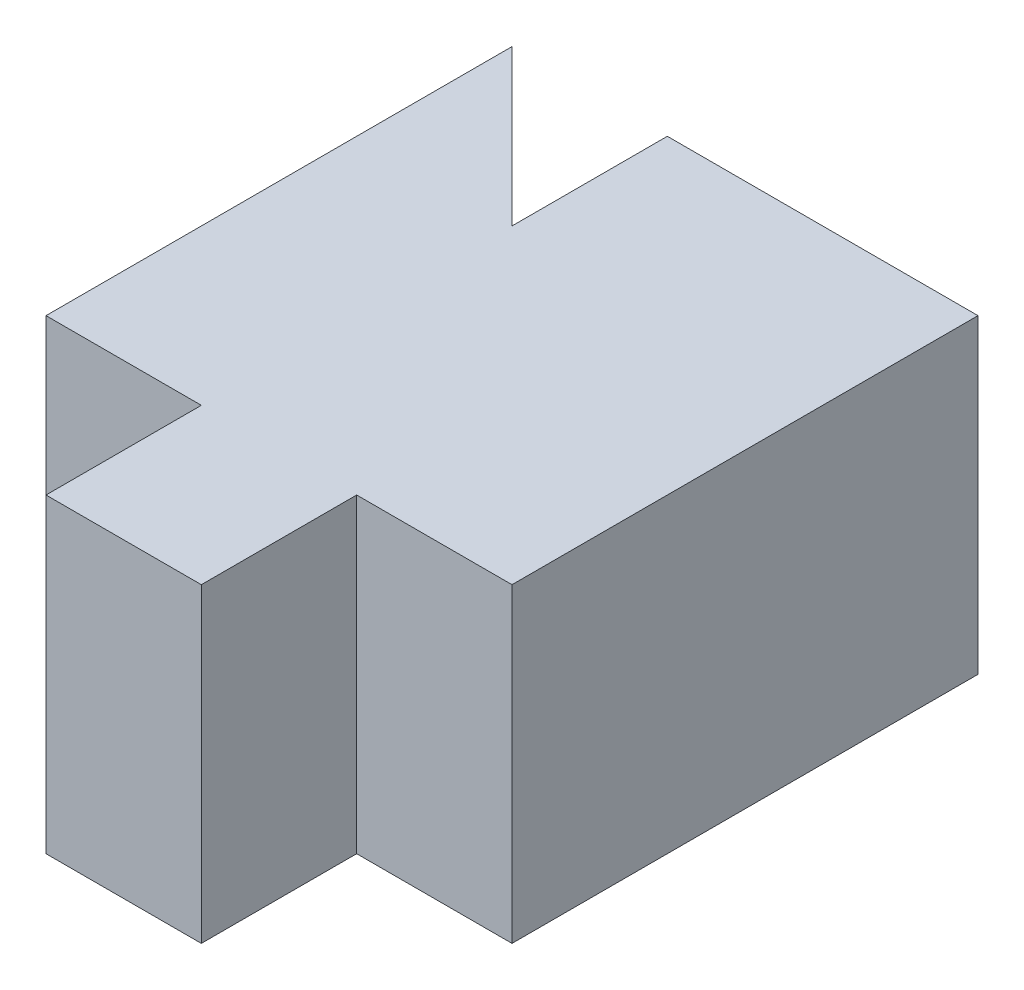
SolidWorks part; units mm, degrees
ref_plane "Front Plane" through (0, 0, 0) normal (0, 0, 1) x (1, 0, 0)
ref_plane "Top Plane" through (0, 0, 0) normal (0, 1, 0) x (1, 0, 0)
ref_plane "Right Plane" through (0, 0, 0) normal (1, 0, 0) x (0, 0, -1)
sketch "Sketch5" plane through (0, 0, 0) normal (0, 1, 0) x (1, 0, 0)
  line L0 (-7.5, 7.5) -> (-2.5, 2.5)
  line L1 (-2.5, 7.5) -> (7.5, 7.5)
  line L2 (-7.5, 7.5) -> (-7.5, -7.5)
  line L3 (-7.5, -7.5) -> (-2.5, -7.5)
  line L4 (7.5, 7.5) -> (7.5, -7.5)
  line L5 (-7.5, 7.5) -> (7.5, -7.5) construction
  line L6 (-7.5, -7.5) -> (7.5, 7.5) construction
  line L7 (-2.5, 2.5) -> (-2.5, 7.5)
  line L8 (-7.5, 7.5) -> (-2.5, 7.5) construction
  line L9 (2.5, -7.5) -> (7.5, -7.5)
  line L11 (-2.5, -7.5) -> (-2.5, -12.5)
  line L12 (-2.5, -12.5) -> (2.5, -12.5)
  line L13 (2.5, -7.5) -> (2.5, -12.5)
  point P0 (0, 0)
  dimension "D1" = 15
  dimension "D2" = 15
  dimension "D3" = 5
  dimension "D4" = 5
  dimension "D5" = 5
  dimension "D6" = 5
extrude "Boss-Extrude1" add sketch "Sketch5" along normal blind 10
